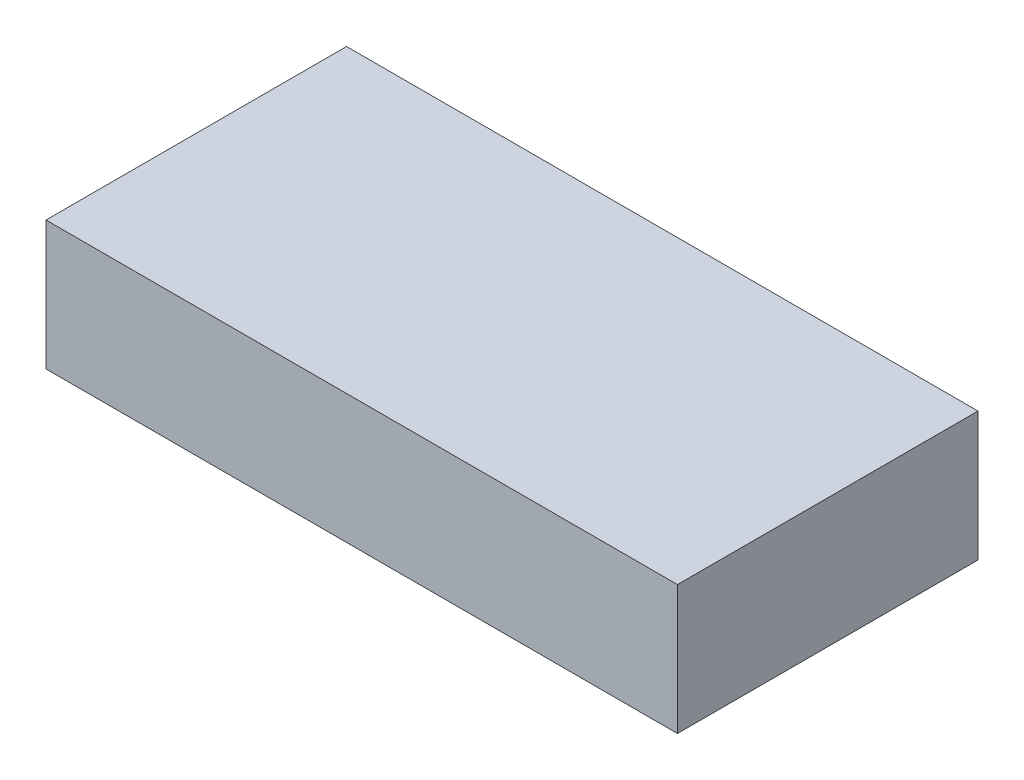
SolidWorks part; units mm, degrees
ref_plane "Front Plane" through (0, 0, 0) normal (0, 0, 1) x (1, 0, 0)
ref_plane "Top Plane" through (0, 0, 0) normal (0, 1, 0) x (1, 0, 0)
ref_plane "Right Plane" through (0, 0, 0) normal (1, 0, 0) x (0, 0, -1)
sketch "Sketch1" plane through (0, 0, 0) normal (0, 1, 0) x (1, 0, 0)
  line L0 (-48.9536, 23.3004) -> (-41.1, 17.11)
  line L1 (41.1, -17.11) -> (-41.1, -17.11)
  line L2 (41.1, -17.11) -> (41.1, 17.11)
  line L3 (41.1, 17.11) -> (-41.1, 17.11)
  line L4 (-41.1, -17.11) -> (-41.1, 17.11)
  line L5 (41.1, -17.11) -> (-41.1, 17.11) construction
  line L6 (41.1, 17.11) -> (-41.1, -17.11) construction
  line L7 (48.9536, -23.3004) -> (-48.9536, -23.3004)
  line L8 (48.9536, -23.3004) -> (48.9536, 23.3004)
  line L9 (48.9536, 23.3004) -> (-48.9536, 23.3004)
  line L10 (-48.9536, -23.3004) -> (-48.9536, 23.3004)
  line L11 (48.9536, -23.3004) -> (-48.9536, 23.3004) construction
  line L12 (48.9536, 23.3004) -> (-48.9536, -23.3004) construction
  point P0 (0, 0)
  point P6 (0, 0)
  dimension "D1" = 82.2
  dimension "D2" = 34.22
  dimension "D3" = 10
extrude "Boss-Extrude1" add sketch "Sketch1" along normal blind 20
sketch "Sketch3" plane through (-48.9536, 0, 0) normal (-1, 0, 0) x (0, 0, 1)
  line L0 (-23.3004, 20) -> (23.3004, 0)
  line L1 (-23.3004, 0) -> (23.3004, 20)
  line L2 (23.3004, 20) -> (-23.3004, 20) construction
  line L3 (17.105, 5.45) -> (-17.105, 5.45)
  line L4 (17.105, 5.45) -> (17.105, 14.55)
  line L5 (17.105, 14.55) -> (-17.105, 14.55)
  line L6 (-17.105, 5.45) -> (-17.105, 14.55)
  line L7 (17.105, 5.45) -> (-17.105, 14.55) construction
  line L8 (17.105, 14.55) -> (-17.105, 5.45) construction
  point P8 (0, 10)
  dimension "D1" = 9.1
  dimension "D2" = 34.21
  dimension "D3" = 5.45
  dimension "D4" = 5.45
extrude "Cut-Extrude1" cut sketch "Sketch3" against normal blind 90 contours L6 L3 L1 L0 L5 | L1 L5 L0 | L3 L0 L1 | L4 L5 L1 L0 L3
sketch "Sketch4" plane through (-48.9536, 0, 0) normal (-1, 0, 0) x (0, 0, 1)
  line L1 (-14.105, 5.45) -> (14.105, 5.45)
  line L6 (-17.105, 10) -> (17.105, 10)
  line L7 (-17.105, 5.45) -> (-17.105, 14.55) construction
  line L8 (17.105, 5.45) -> (17.105, 14.55) construction
  line L9 (-14.105, 5.45) -> (-14.105, 2.45)
  line L10 (14.105, 5.45) -> (14.105, 2.45)
  line L11 (-14.105, 2.45) -> (14.105, 2.45)
  line L12 (17.105, 5.45) -> (-17.105, 5.45) construction
  line L13 (-17.105, 5.45) -> (17.105, 5.45)
  line L14 (-17.105, 5.45) -> (-17.105, 4.45)
  line L15 (17.105, 5.45) -> (17.105, 4.45)
  line L16 (-17.105, 4.45) -> (17.105, 4.45)
  line L17 (17.105, 10) -> (17.105, 4.45)
  line L19 (17.105, 4.45) -> (18.105, 4.45)
  line L21 (-17.105, 10) -> (-17.105, 4.45)
  line L23 (-17.105, 4.45) -> (-17.955, 4.45)
  line L25 (-17.105, 14.55) -> (-17.105, 4.45)
  line L26 (-17.105, 14.55) -> (-17.955, 14.55)
  line L27 (-17.105, 4.45) -> (-17.955, 4.45)
  line L28 (-17.955, 14.55) -> (-17.955, 4.45)
  line L29 (17.105, 14.55) -> (17.105, 4.45)
  line L30 (17.105, 14.55) -> (17.955, 14.55)
  line L31 (17.105, 4.45) -> (17.955, 4.45)
  line L32 (17.955, 14.55) -> (17.955, 4.45)
  line L33 (-17.955, 14.55) -> (17.955, 14.55)
  line L34 (-17.955, 14.55) -> (-17.955, 15.55)
  line L35 (17.955, 14.55) -> (17.955, 15.55)
  line L36 (-17.955, 15.55) -> (17.955, 15.55)
  line L37 (23.3004, 20) -> (-23.3004, 20) construction
  line M10 (17.105, 14.55) -> (17.105, 5.45)
  line M11 (17.105, 5.45) -> (-17.105, 5.45)
  line M12 (-17.105, 5.45) -> (-17.105, 14.55)
  dimension "D1" = 3
  dimension "D2" = 3
  dimension "D3" = 3
  dimension "D4" = 1
  dimension "D5" = 0.85
  dimension "D6" = 0.85
  dimension "D7" = 0.85
  dimension "D8" = 1
  dimension "D9" = 5.45
extrude "Cut-Extrude3" cut sketch "Sketch4" against normal blind 90 contours L9 L11 L10 M11 | L26 L28 L23 L14 M12 | L32 L30 L15 L19 M10 | L14 L16 L9 M11 | L10 L16 L15 M11 | L16 L9 L11 L10
